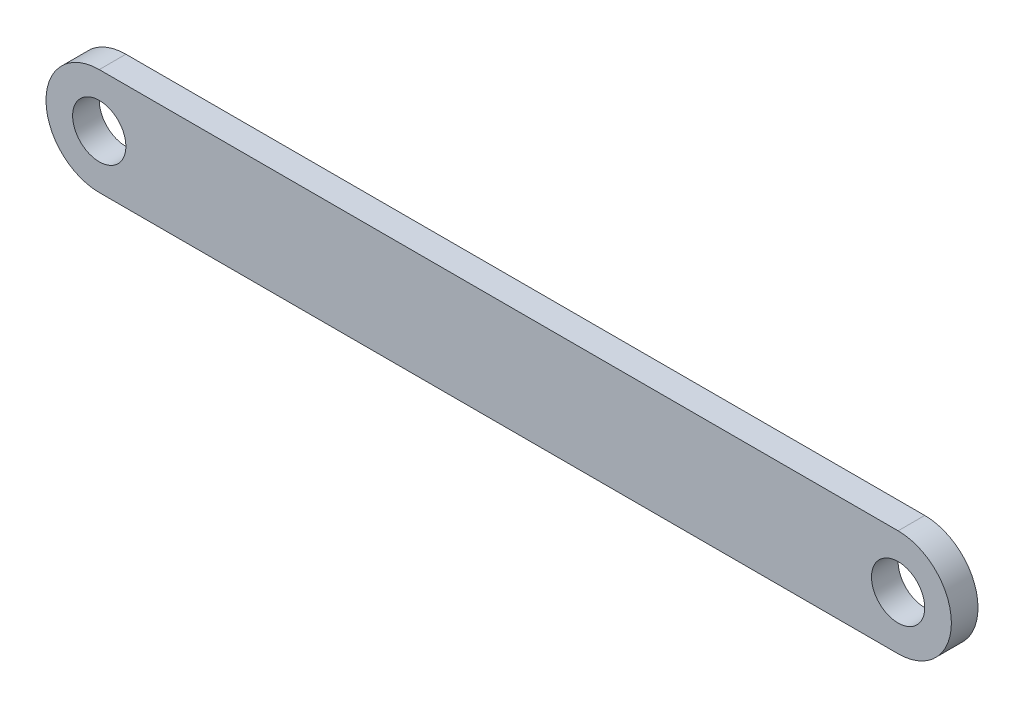
SolidWorks part; units mm, degrees
ref_plane "Front Plane" through (0, 0, 0) normal (0, 0, 1) x (1, 0, 0)
ref_plane "Top Plane" through (0, 0, 0) normal (0, 1, 0) x (1, 0, 0)
ref_plane "Right Plane" through (0, 0, 0) normal (1, 0, 0) x (0, 0, -1)
sketch "Sketch1" plane through (0, 0, 0) normal (0, 0, 1) x (1, 0, 0)
  line L0 (-425.2396, 0.1574) -> (49574.7604, 0.1574) construction
  line L1 (0, 0) -> (0, 71.3201) construction
  line L2 (-476.25, 63.6574) -> (476.25, 63.6574)
  line L3 (-476.25, -63.3426) -> (476.25, -63.3426)
  arc A0 (-476.25, 63.6574) -> (-476.25, -63.3426) centre (-476.25, 0.1574) ccw
  arc A1 (476.25, -63.3426) -> (476.25, 63.6574) centre (476.25, 0.1574) ccw
  circle A2 centre (-476.25, 0.1574) radius 31.75
  circle A3 centre (476.25, 0.1574) radius 31.75
  dimension "D2" = 63.5
  dimension "D3" = 63.5
  dimension "D1" = 952.5
extrude "Boss-Extrude1" add sketch "Sketch1" along normal mid plane 31.75
